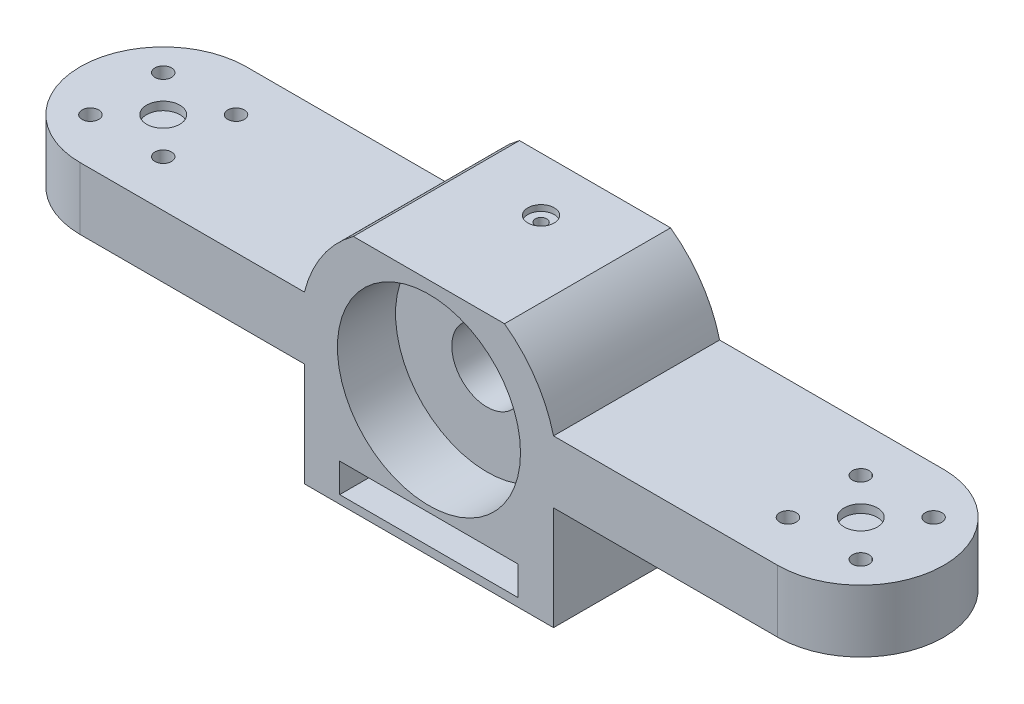
SolidWorks part; units mm, degrees
material "6061 Alloy"
ref_plane "Front Plane" through (0, 0, 0) normal (0, 0, 1) x (1, 0, 0)
ref_plane "Top Plane" through (0, 0, 0) normal (0, 1, 0) x (1, 0, 0)
ref_plane "Right Plane" through (0, 0, 0) normal (1, 0, 0) x (0, 0, -1)
sketch "Sketch1" plane through (0, 0, 0) normal (0, 1, 0) x (1, 0, 0)
  line L1 (-42, -10) -> (42, -10)
  line L3 (-42, 10) -> (42, 10)
  line L5 (-42, -10) -> (42, 10) construction
  line L6 (-42, 10) -> (42, -10) construction
  arc A0 (-42, 10) -> (-42, -10) centre (-42, 0) ccw
  arc A1 (42, -10) -> (42, 10) centre (42, 0) ccw
  point P0 (0, 0)
  point P7 (52, 0)
  dimension "D3" = 10
  dimension "D1" = 84
  dimension "D2" = 20
  dimension "D4" = 10
extrude "Boss-Extrude1" add sketch "Sketch1" along normal blind 25
sketch "Sketch2" plane through (0, 0, 10) normal (0, 0, 1) x (1, 0, 0)
  line L0 (0, 0) -> (0, 12.5) construction
  circle A0 centre (0, 12.5) radius 11.025
  dimension "D2" = 22.05
  dimension "D1" = 12.5
extrude "Cut-Extrude1" cut sketch "Sketch2" against normal blind 7
sketch "Sketch3" plane through (0, 0, 0) normal (0, -1, 0) x (1, 0, 0)
  line L0 (-42, 10) -> (42, 10) construction
  line L2 (15, -10) -> (15, 10)
  line L4 (-15, -10) -> (-15, 10)
  line L5 (15, -10) -> (-15, 10) construction
  line L6 (15, 10) -> (-15, -10) construction
  line L7 (-15, 10) -> (-42, 10)
  line L8 (-42, -10) -> (-15, -10)
  line L9 (15, 10) -> (42, 10)
  line L10 (15, -10) -> (42, -10)
  arc A0 (-42, 10) -> (-42, -10) centre (-42, 0) ccw
  arc A1 (42, -10) -> (42, 10) centre (42, 0) ccw
  point P7 (0, 0)
extrude "Cut-Extrude3" cut sketch "Sketch3" against normal blind 8.75
sketch "Sketch4" plane through (0, 25, 0) normal (0, 1, 0) x (1, 0, 0)
  line L0 (15, -10) -> (15, 10)
  line L1 (-15, -10) -> (-15, 10)
  line L2 (15, -10) -> (-15, 10) construction
  line L3 (15, 10) -> (-15, -10) construction
  line L4 (-15, 10) -> (-55, 10)
  line L5 (-55, -10) -> (-15, -10)
  line L6 (15, 10) -> (55, 10)
  line L7 (15, -10) -> (55, -10)
  arc A0 (-55, 10) -> (-55, -10) centre (-55, 0) ccw
  arc A1 (55, -10) -> (55, 10) centre (55, 0) ccw
  point P2 (0, 0)
  dimension "D1" = 0
  dimension "D2" = 0
extrude "Cut-Extrude5" cut sketch "Sketch4" against normal blind 8.75
sketch "Sketch5" plane through (0, 16.25, 0) normal (0, 1, 0) x (1, 0, 0)
  line L0 (0, 0) -> (-42, 0) construction
  line L1 (-42, 0) -> (-37.6159, 4.3841) construction
  line L2 (-42, 0) -> (-46.3841, 4.3841) construction
  line L3 (-42, 0) -> (-46.3841, -4.3841) construction
  line L4 (-42, 0) -> (-37.6159, -4.3841) construction
  line L5 (0, 0) -> (42, 0) construction
  line L6 (42, 0) -> (46.3841, 4.3841) construction
  line L7 (42, 0) -> (37.6159, 4.3841) construction
  line L8 (42, 0) -> (37.6159, -4.3841) construction
  line L9 (42, 0) -> (46.3841, -4.3841) construction
  circle A0 centre (-46.3841, 4.3841) radius 1
  circle A1 centre (-37.6159, 4.3841) radius 1
  circle A2 centre (-37.6159, -4.3841) radius 1
  circle A3 centre (-46.3841, -4.3841) radius 1
  circle A4 centre (37.6159, 4.3841) radius 1
  circle A5 centre (46.3841, 4.3841) radius 1
  circle A6 centre (46.3841, -4.3841) radius 1
  circle A7 centre (37.6159, -4.3841) radius 1
  dimension "D3" = 2
  dimension "D4" = 2
  dimension "D5" = 2
  dimension "D6" = 2
  dimension "D13" = 2
  dimension "D14" = 2
  dimension "D15" = 2
  dimension "D16" = 2
  dimension "D1" = 6.2
  dimension "D2" = 6.2
  dimension "D7" = 6.2
  dimension "D8" = 6.2
  dimension "D9" = 0
  dimension "D10" = 0
  dimension "D11" = 6.2
  dimension "D12" = 6.2
  dimension "D17" = 6.2
  dimension "D18" = 6.2
  dimension "D19" = 0
  dimension "D20" = 0
  dimension "D21" = 45
  dimension "D22" = 90
  dimension "D23" = 90
  dimension "D24" = 90
  dimension "D25" = 45
  dimension "D26" = 90
  dimension "D27" = 90
  dimension "D28" = 90
extrude "Cut-Extrude6" cut sketch "Sketch5" against normal blind 7.5
sketch "Sketch6" plane through (0, 8.75, 0) normal (0, -1, 0) x (1, 0, 0)
  line L0 (0, 0) -> (-42, 0) construction
  line L1 (-42, 0) -> (-35.8, 0) construction
  line L2 (-42, 0) -> (-48.2, 0) construction
  line L3 (-42, 0) -> (-42, 6.2) construction
  line L4 (-42, 0) -> (-42, -6.2) construction
  line L5 (-48.2, 0) -> (-35.8, 0) construction
  line L6 (0, 0) -> (42, 0) construction
  line L7 (42, 0) -> (48.2, 0) construction
  line L8 (42, 0) -> (35.8, 0) construction
  line L9 (42, 0) -> (42, 6.2) construction
  line L10 (42, 0) -> (42, -6.2) construction
  line L11 (35.8, 0) -> (48.2, 0) construction
  circle A0 centre (-42, 6.2) radius 1.95
  circle A1 centre (-35.8, 0) radius 1.95
  circle A2 centre (-48.2, 0) radius 1.95
  circle A3 centre (-42, -6.2) radius 1.95
  circle A4 centre (42, 6.2) radius 1.95
  circle A5 centre (48.2, 0) radius 1.95
  circle A6 centre (35.8, 0) radius 1.95
  circle A7 centre (42, -6.2) radius 1.95
  dimension "D5" = 3.9
  dimension "D6" = 3.9
  dimension "D7" = 3.9
  dimension "D8" = 3.9
  dimension "D15" = 3.9
  dimension "D16" = 3.9
  dimension "D17" = 3.9
  dimension "D18" = 3.9
  dimension "D1" = 6.2
  dimension "D2" = 6.2
  dimension "D3" = 6.2
  dimension "D4" = 6.2
  dimension "D9" = 0
  dimension "D10" = 0
  dimension "D11" = 6.2
  dimension "D12" = 6.2
  dimension "D13" = 6.2
  dimension "D14" = 6.2
  dimension "D19" = 0
  dimension "D20" = 0
  dimension "D21" = 42
extrude "Cut-Extrude7" cut sketch "Sketch6" against normal offset from surface (6.5 mm away) 1 up to face at (-46.3841, 16.25, -3.3841)
sketch "Sketch7" plane through (0, 16.25, 0) normal (0, 1, 0) x (1, 0, 0)
  line L0 (0, 0) -> (-42, 0) construction
  line L1 (0, 0) -> (42, 0) construction
  circle A0 centre (-42, 0) radius 2
  circle A1 centre (42, 0) radius 2
  dimension "D1" = 4
  dimension "D2" = 4
extrude "Cut-Extrude8" cut sketch "Sketch7" against normal blind 1
sketch "Sketch8" plane through (0, 0, 10) normal (0, 0, 1) x (1, 0, 0)
  line L0 (0, 0) -> (0, 12.5) construction
  line L1 (-15, 16.25) -> (-15, 25)
  line L2 (15, 0) -> (9.1001, 0)
  line L3 (15, 0) -> (15, 8.75)
  line L4 (15, 25) -> (9.1001, 25)
  line L5 (-15, 0) -> (-15, 8.75)
  line L6 (15, 0) -> (-15, 25) construction
  line L7 (15, 25) -> (-15, 0) construction
  line L8 (-9.1001, 25) -> (-15, 25)
  line L9 (15, 16.25) -> (15, 25)
  line L10 (-9.1001, 0) -> (-15, 0)
  arc A0 (-15, 8.75) -> (-9.1001, 0) centre (0, 12.5) ccw
  arc A1 (-9.1001, 25) -> (-15, 16.25) centre (0, 12.5) ccw
  arc A2 (15, 16.25) -> (9.1001, 25) centre (0, 12.5) ccw
  arc A3 (9.1001, 0) -> (15, 8.75) centre (0, 12.5) ccw
  dimension "D1" = 12.5
extrude "Cut-Extrude9" cut sketch "Sketch8" against normal through all
sketch "Sketch9" plane through (0, 0, 3) normal (0, 0, 1) x (1, 0, 0)
  line L0 (0, 0) -> (0, 12.5) construction
  line L1 (-9.1001, 0) -> (9.1001, 0) construction
  circle A0 centre (0, 12.5) radius 4.25
  dimension "D1" = 8.5
extrude "Cut-Extrude10" cut sketch "Sketch9" against normal up to next contours A0
hole_wizard "CBORE for #00 Binding Head Machine Screw2" positions "Sketch17" profile "Sketch18" counterbore size "#00" standard "ANSI Inch"
sketch "Sketch17" plane through (0, 25, 0) normal (0, 1, 0) x (1, 0, 0)
  line L0 (9.1001, 10) -> (-9.1001, 10) construction
  point P0 (0, 3.5)
  dimension "D1" = 6.5
sketch "Sketch18" plane through (0, 25, -3.5) normal (1, 0, 0) x (0, 0, 1)
  line L0 (0, 0) -> (0, 25.4197)
  line L1 (0, 25.4197) -> (0.6985, 25)
  line L2 (0.6985, 25) -> (0.6985, 0.7112)
  line L3 (0.6985, 0.7112) -> (1.5875, 0.7112)
  line L4 (1.5875, 0.7112) -> (1.5875, 0)
  line L5 (1.5875, 0) -> (0, 0)
  line L10 (0, 25.4197) -> (-0.6985, 25) construction
  line L11 (0, -6.35) -> (0, 107.95) construction
  dimension "Hole Dia." = 1.397
  dimension "Hole Depth" = 25
  dimension "C'Bore Dia." = 3.175
  dimension "C'Bore Depth" = 0.7112
  dimension "Drill Angle" = 118
sketch "Sketch19" plane through (0, 0, -10) normal (0, 0, -1) x (-1, 0, 0)
  line L0 (-9.1001, 0) -> (9.1001, 0)
  line L2 (-15, 8.75) -> (-15, -3.75)
  line L3 (-15, -3.75) -> (15, -3.75)
  line L4 (15, 8.75) -> (15, -3.75)
  arc A0 (-15, 8.75) -> (-9.1001, 0) centre (0, 12.5) ccw
  arc A1 (9.1001, 0) -> (15, 8.75) centre (0, 12.5) ccw
  dimension "D1" = 12.5
  dimension "D2" = 30
extrude "Boss-Extrude4" add sketch "Sketch19" against normal through all
sketch "Sketch20" plane through (0, 0, 10) normal (0, 0, 1) x (1, 0, 0)
  line L1 (-10.75, -2.75) -> (10.75, -2.75)
  line L2 (-10.75, -2.75) -> (-10.75, 0.75)
  line L3 (-10.75, 0.75) -> (10.75, 0.75)
  line L4 (10.75, -2.75) -> (10.75, 0.75)
  line L5 (-10.75, -2.75) -> (10.75, 0.75) construction
  line L6 (-10.75, 0.75) -> (10.75, -2.75) construction
  point P0 (0, -1)
  point P5 (0, -0.9787)
  point P6 (0, -1.1652)
  point P7 (2.603, -1.3886)
  dimension "D1" = 3.5
  dimension "D2" = 21.5
  dimension "D3" = 0
  dimension "D4" = 1
extrude "Cut-Extrude13" cut sketch "Sketch20" against normal blind 16.5
